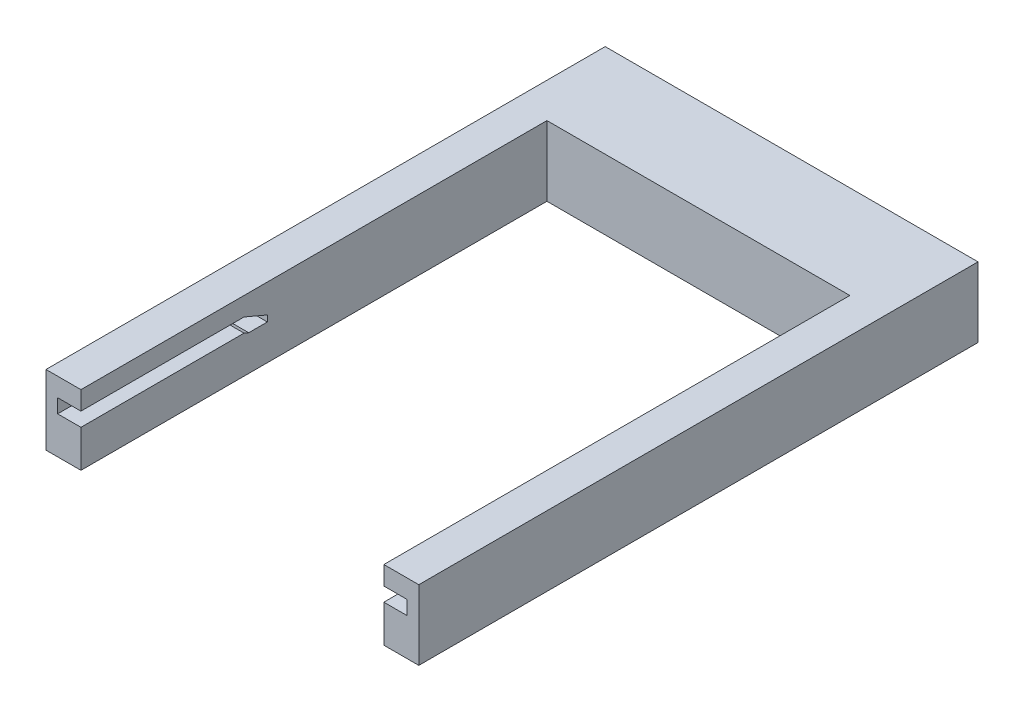
SolidWorks part; units mm, degrees
ref_plane "Front Plane" through (0, 0, 0) normal (0, 0, 1) x (1, 0, 0)
ref_plane "Top Plane" through (0, 0, 0) normal (0, 1, 0) x (1, 0, 0)
ref_plane "Right Plane" through (0, 0, 0) normal (1, 0, 0) x (0, 0, -1)
sketch "Sketch1" plane through (0, 0, 0) normal (0, 1, 0) x (1, 0, 0)
  line L0 (32.5, -60) -> (40, -60)
  line L1 (-40, 60) -> (40, 60)
  line L2 (-40, 60) -> (-40, -60)
  line L3 (-40, -60) -> (-32.5, -60)
  line L4 (40, 60) -> (40, -60)
  line L5 (-40, 60) -> (40, -60) construction
  line L6 (-40, -60) -> (40, 60) construction
  line L7 (-32.5, 40) -> (32.5, 40)
  line L8 (-32.5, 40) -> (-32.5, -60)
  line L10 (32.5, 40) -> (32.5, -60)
  line L11 (-32.5, 40) -> (32.5, -60) construction
  line L12 (-32.5, -60) -> (32.5, 40) construction
  point P0 (0, 0)
  point P6 (0, -10)
  point P11 (0, -9.9523)
  point P12 (0, 0)
  dimension "D1" = 80
  dimension "D2" = 120
  dimension "D3" = 100
  dimension "D4" = 65
extrude "Boss-Extrude1" add sketch "Sketch1" along normal blind 15
sketch "Sketch2" plane through (0, 0, 0) normal (1, 0, 0) x (0, 0, -1)
  line L0 (-60, 11) -> (-25, 11)
  line L1 (-60, 15) -> (-60, 0) construction
  line L2 (-25, 11) -> (-20, 8.8776)
  line L3 (-20, 8.8776) -> (-20, 7.5755)
  line L4 (-20, 7.5755) -> (-24, 7.5755)
  line L5 (-24, 7.5755) -> (-25, 8)
  line L6 (-25, 8) -> (-60, 8)
  line L7 (-60, 8) -> (-60, 11)
  line L9 (-60, 0) -> (60, 0) construction
  dimension "D1" = 3
  dimension "D2" = 35
  dimension "D3" = 23
  dimension "D4" = 40
  dimension "D5" = 4
  dimension "D6" = 8
extrude "Cut-Extrude1" cut sketch "Sketch2" against normal mid plane 75
